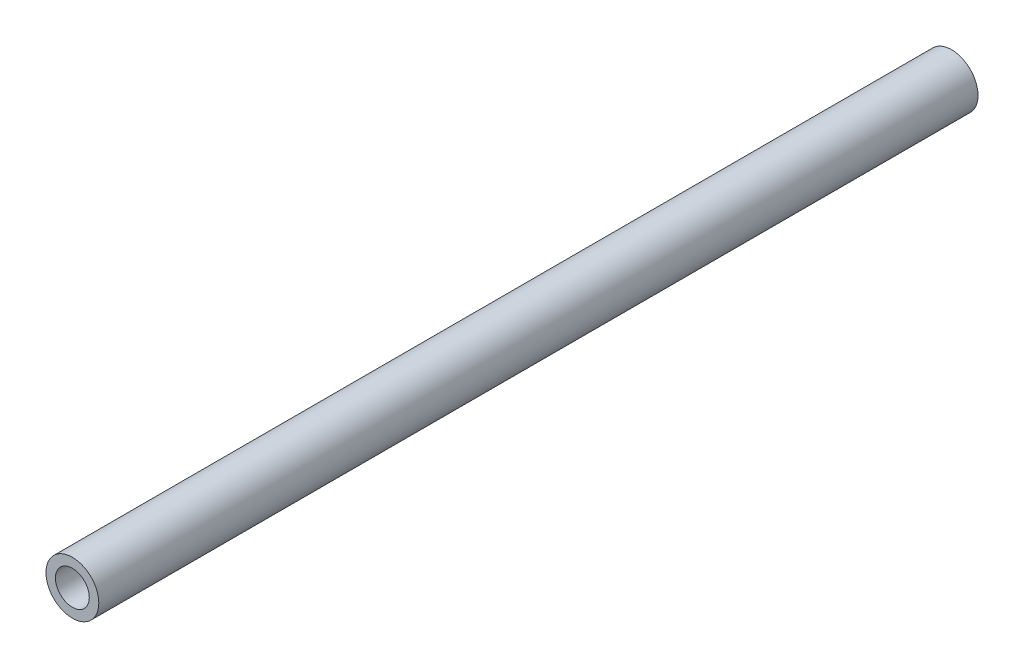
SolidWorks part; units mm, degrees
material "6061 合金"
ref_plane "前视基准面" through (0, 0, 0) normal (0, 0, 1) x (1, 0, 0)
ref_plane "上视基准面" through (0, 0, 0) normal (0, 1, 0) x (1, 0, 0)
ref_plane "右视基准面" through (0, 0, 0) normal (1, 0, 0) x (0, 0, -1)
sketch "草图1" plane through (0, 0, 0) normal (0, 0, 1) x (1, 0, 0)
  circle A0 centre (0, 0) radius 2.5
  circle A1 centre (0, 0) radius 1.6
  dimension "D1" = 3.2
  dimension "D2" = 5
extrude "凸台-拉伸1" add sketch "草图1" along normal blind 83.18
